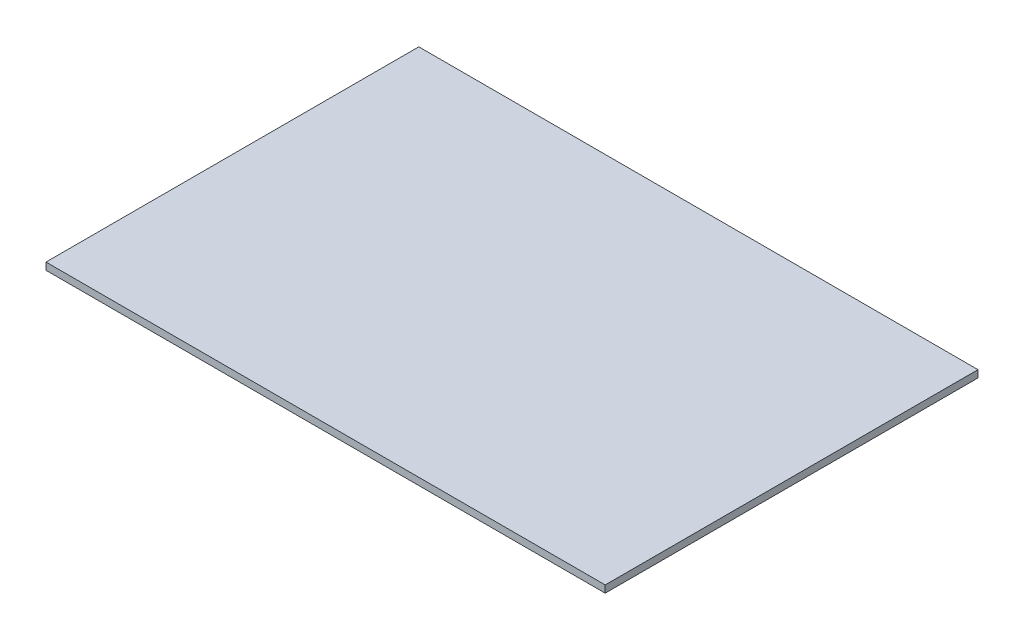
SolidWorks part; units mm, degrees
ref_plane "Спереди" through (0, 0, 0) normal (0, 0, 1) x (1, 0, 0)
ref_plane "Сверху" through (0, 0, 0) normal (0, 1, 0) x (1, 0, 0)
ref_plane "Справа" through (0, 0, 0) normal (1, 0, 0) x (0, 0, -1)
sketch "Эскиз1" plane through (0, 0, 0) normal (0, 1, 0) x (1, 0, 0)
  line L1 (0, 0) -> (-780, 0)
  line L2 (0, 0) -> (0, 520)
  line L3 (0, 520) -> (-780, 520)
  line L4 (-780, 0) -> (-780, 520)
  dimension "D1" = 520
  dimension "D2" = 780
extrude "Бобышка-Вытянуть2" add sketch "Эскиз1" along normal blind 10
